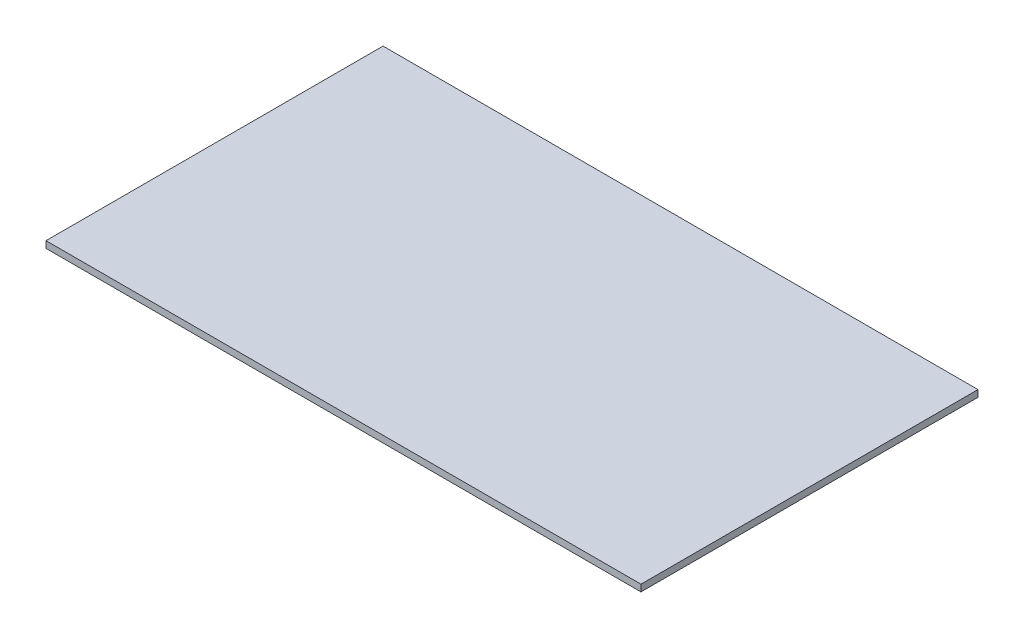
SolidWorks part; units mm, degrees
ref_plane "Front Plane" through (0, 0, 0) normal (0, 0, 1) x (1, 0, 0)
ref_plane "Top Plane" through (0, 0, 0) normal (0, 1, 0) x (1, 0, 0)
ref_plane "Right Plane" through (0, 0, 0) normal (1, 0, 0) x (0, 0, -1)
sketch "Sketch1" plane through (0, 0, 0) normal (0, 1, 0) x (1, 0, 0)
  line L1 (-44.29, -25.09) -> (44.29, -25.09)
  line L2 (-44.29, -25.09) -> (-44.29, 25.09)
  line L3 (-44.29, 25.09) -> (44.29, 25.09)
  line L4 (44.29, -25.09) -> (44.29, 25.09)
  line L5 (-44.29, -25.09) -> (44.29, 25.09) construction
  line L6 (-44.29, 25.09) -> (44.29, -25.09) construction
  point P0 (0, 0)
  dimension "D1" = 50.18
  dimension "D2" = 88.58
extrude "Boss-Extrude1" add sketch "Sketch1" along normal blind 1
